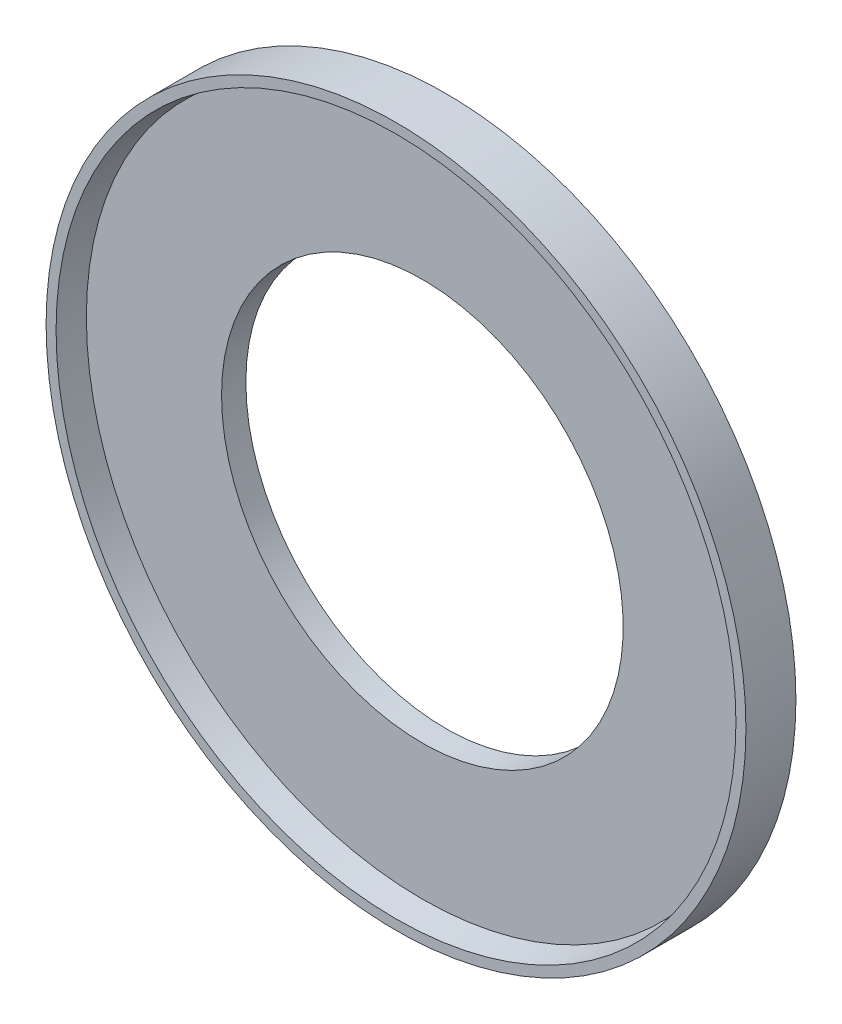
SolidWorks part; units mm, degrees
ref_plane "정면" through (0, 0, 0) normal (0, 0, 1) x (1, 0, 0)
ref_plane "윗면" through (0, 0, 0) normal (0, 1, 0) x (1, 0, 0)
ref_plane "우측면" through (0, 0, 0) normal (1, 0, 0) x (0, 0, -1)
sketch "스케치2" plane through (0, 0, 0) normal (0, 1, 0) x (1, 0, 0)
  line L0 (6.7214, -0.4727) -> (6.8, -1)
  line L1 (6.8, -1) -> (7, -1)
  line L2 (7, -1) -> (7, 0)
  line L3 (7, 0) -> (6.7, 0)
  line L4 (6.7, 0) -> (0, 0) construction
  line L5 (0, 0) -> (0, -4.0437) construction
  line L6 (6.7, 0) -> (6.4954, -0.2727)
  line L7 (6.4954, -0.2727) -> (4.1237, -0.2727)
  line L8 (4.1237, -0.2727) -> (4.0851, 0)
  line L9 (4.0851, 0) -> (4.0036, 0)
  line L10 (4.0036, 0) -> (4.0173, -0.4727)
  line L11 (4.0173, -0.4727) -> (6.7214, -0.4727)
  dimension "D1" = 0.3
  dimension "D2" = 0.2
  dimension "D3" = 1
  dimension "D4" = 14
  dimension "D5" = 0.2
revolve "회전1" add sketch "스케치2" angle 360 about L5
